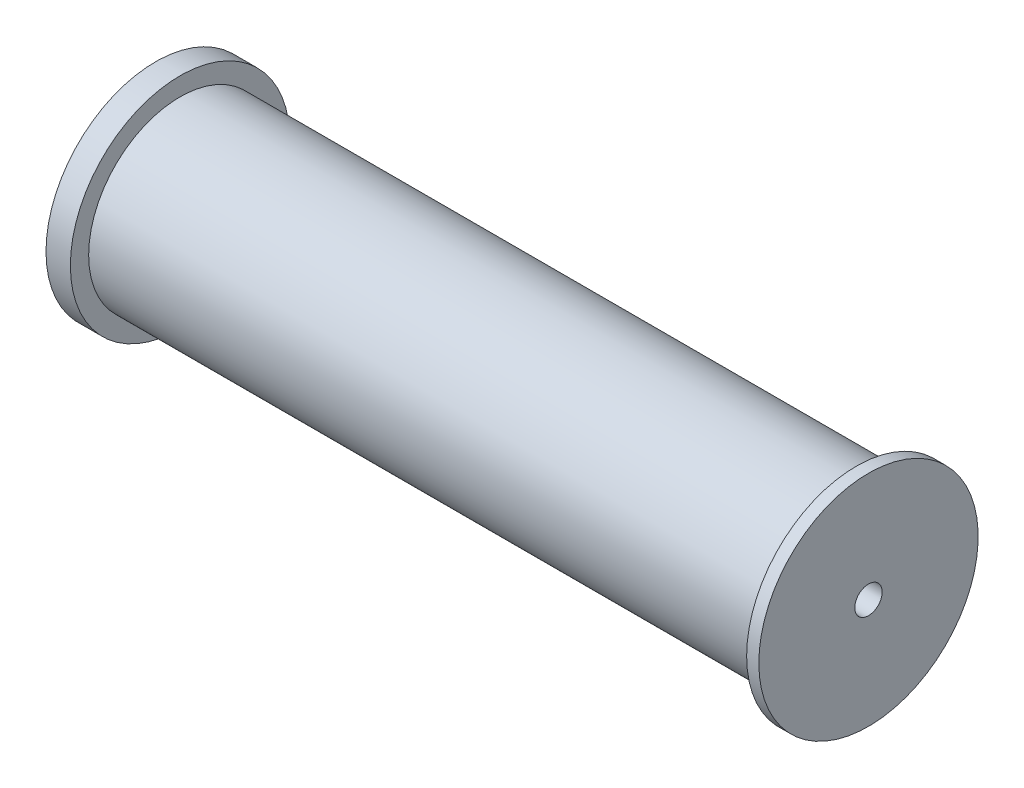
SolidWorks part; units mm, degrees
ref_plane "Plan de face" through (0, 0, 0) normal (0, 0, 1) x (1, 0, 0)
ref_plane "Plan de dessus" through (0, 0, 0) normal (0, 1, 0) x (1, 0, 0)
ref_plane "Plan de droite" through (0, 0, 0) normal (1, 0, 0) x (0, 0, -1)
sketch "Esquisse2" plane through (0, 0, 0) normal (0, 0, 1) x (1, 0, 0)
  line L0 (4, 18) -> (0, 18)
  line L1 (0, 18) -> (0, 0)
  line L4 (4, 18) -> (4, 15)
  line L5 (4, 15) -> (115, 15)
  line L6 (115, 15) -> (115, 18)
  line L7 (115, 18) -> (117, 18)
  line L8 (117, 18) -> (117, 0)
  line L9 (117, 0) -> (0, 0)
  line L10 (-23.4383, 0) -> (159.8231, 0) construction
  dimension "D1" = 111
  dimension "D2" = 2
  dimension "D3" = 4
  dimension "D4" = 15
revolve "Révolution1" add sketch "Esquisse2" angle 360 about L10
sketch "Esquisse4" plane through (0, 0, 0) normal (-1, 0, 0) x (0, 0, 1)
  circle A0 centre (0, 0) radius 2.25
  dimension "D1" = 4.5
extrude "Enlèv. mat.-Extru.2" cut sketch "Esquisse4" against normal through all
